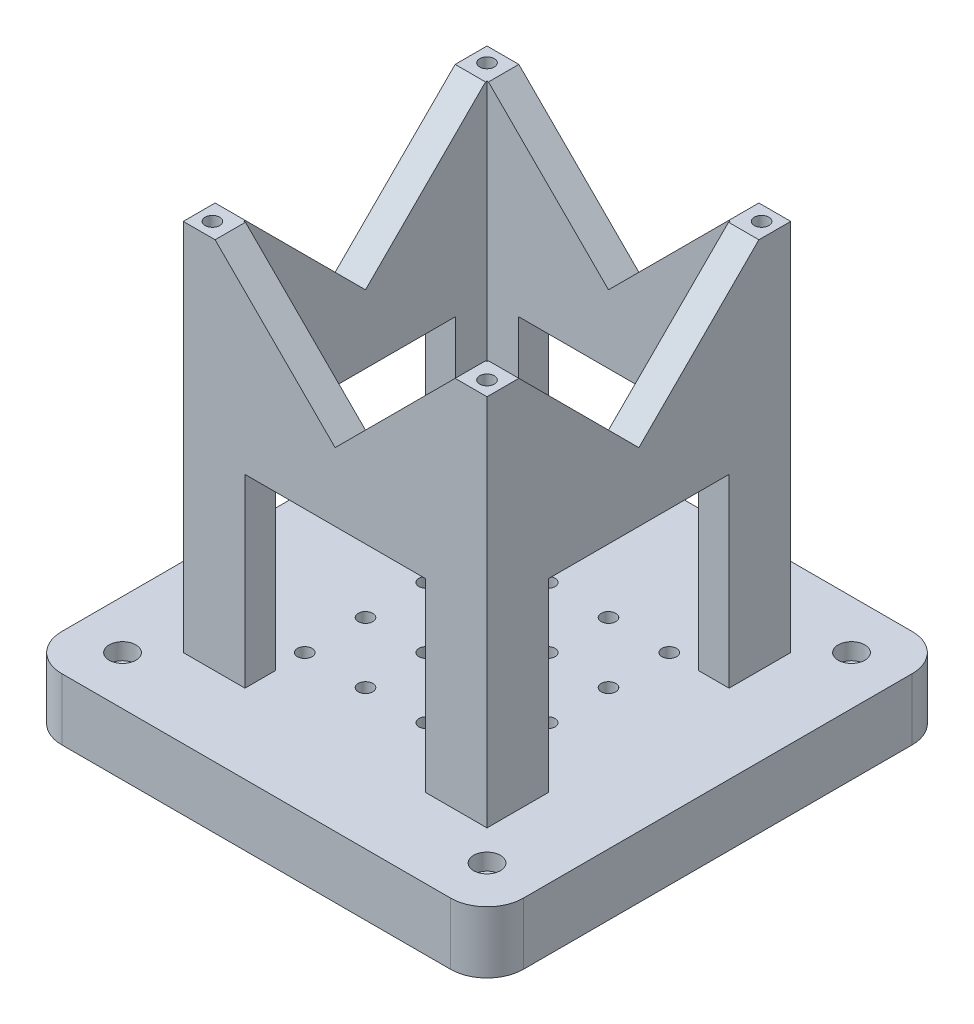
SolidWorks part; units mm, degrees
ref_plane "Front Plane" through (0, 0, 0) normal (0, 0, 1) x (1, 0, 0)
ref_plane "Top Plane" through (0, 0, 0) normal (0, 1, 0) x (1, 0, 0)
ref_plane "Right Plane" through (0, 0, 0) normal (1, 0, 0) x (0, 0, -1)
sketch "Sketch2" plane through (0, 0, 0) normal (0, 1, 0) x (1, 0, 0)
  line L1 (15, 0) -> (175, 0)
  line L2 (0, 15) -> (0, 175)
  line L3 (15, 190) -> (175, 190)
  line L4 (190, 15) -> (190, 175)
  arc A0 (15, 190) -> (0, 175) centre (15, 175) ccw
  arc A1 (0, 15) -> (15, 0) centre (15, 15) ccw
  arc A2 (175, 0) -> (190, 15) centre (175, 15) ccw
  arc A3 (175, 190) -> (190, 175) centre (175, 175) cw
  point P6 (0, 190)
  point P9 (0, 0)
  point P12 (190, 0)
  point P15 (190, 190)
  dimension "D3" = 15
  dimension "D1" = 190
  dimension "D2" = 190
extrude "Extrude2" add sketch "Sketch2" along normal blind 25.4
sketch "Sketch3" plane through (0, 25.4, 0) normal (0, 1, 0) x (-1, 0, 0)
  line L1 (-157.5, -157.5) -> (-32.5, -157.5)
  line L2 (-157.5, -157.5) -> (-157.5, -32.5)
  line L3 (-157.5, -32.5) -> (-32.5, -32.5)
  line L4 (-32.5, -157.5) -> (-32.5, -32.5)
  line L8 (-32.5, -157.5) -> (0, -157.5) construction
  line L9 (0, -175) -> (0, -15) construction
  line L10 (-157.5, -157.5) -> (-190, -157.5) construction
  line L11 (-190, -15) -> (-190, -175) construction
  line L12 (-157.5, -32.5) -> (-157.5, 0) construction
  line L13 (-15, 0) -> (-175, 0) construction
  line L14 (-157.5, -157.5) -> (-157.5, -190) construction
  line L15 (-175, -190) -> (-15, -190) construction
  dimension "D1" = 125
  dimension "D2" = 125
extrude "Extrude3" add sketch "Sketch3" along normal blind 153.67
sketch "Sketch4" plane through (0, 179.07, 0) normal (0, 1, 0) x (-1, 0, 0)
  line L0 (-157.5, -32.5) -> (-157.5, -157.5) construction
  line L1 (-145, -145) -> (-45, -145)
  line L2 (-145, -145) -> (-145, -45)
  line L3 (-145, -45) -> (-45, -45)
  line L4 (-45, -145) -> (-45, -45)
  line L5 (-157.5, -157.5) -> (-32.5, -157.5) construction
  line L6 (-32.5, -157.5) -> (-32.5, -32.5) construction
  line L7 (-32.5, -32.5) -> (-157.5, -32.5) construction
  point P4 (-157.5, -95)
  dimension "D1" = 12.5
  dimension "D2" = 12.5
  dimension "D3" = 12.5
  dimension "D4" = 12.5
extrude "Cut-Extrude1" cut sketch "Sketch4" against normal blind 153.67
sketch "Sketch5" plane through (0, 0, -32.5) normal (0, 0, 1) x (1, 0, 0)
  line L0 (45.6086, 179.07) -> (144.3914, 179.07)
  line L1 (32.5, 179.07) -> (157.5, 179.07) construction
  line L2 (144.3914, 179.07) -> (95, 129.6786)
  line L3 (95, 129.6786) -> (45.6086, 179.07)
  line L4 (32.5, 179.07) -> (32.5, 25.4) construction
  line L5 (157.5, 179.07) -> (157.5, 25.4) construction
  line L6 (15, 25.4) -> (175, 25.4) construction
  line L7 (57.9, 101.6) -> (132.1, 101.6)
  line L8 (57.9, 101.6) -> (57.9, 25.4)
  line L9 (57.9, 25.4) -> (132.1, 25.4)
  line L10 (132.1, 101.6) -> (132.1, 25.4)
  line L11 (32.5, 129.6786) -> (157.5, 129.6786) construction
  point P17 (95, 129.6786)
  dimension "D1" = 135
  dimension "D3" = 49.3914
  dimension "D4" = 25.4
  dimension "D5" = 25.4
  dimension "D6" = 76.2
extrude "Cut-Extrude2" cut sketch "Sketch5" against normal through all
sketch "Sketch6" plane through (157.5, 0, 0) normal (1, 0, 0) x (0, 0, -1)
  line L0 (45.6086, 179.07) -> (144.3914, 179.07)
  line L1 (32.5, 179.07) -> (157.5, 179.07) construction
  line L2 (144.3914, 179.07) -> (95, 129.6786)
  line L3 (95, 129.6786) -> (45.6086, 179.07)
  line L6 (175, 25.4) -> (15, 25.4) construction
  line L7 (132.1, 101.6) -> (57.9, 101.6)
  line L8 (132.1, 101.6) -> (132.1, 25.4)
  line L9 (132.1, 25.4) -> (57.9, 25.4)
  line L10 (57.9, 101.6) -> (57.9, 25.4)
  line L11 (157.5, 179.07) -> (157.5, 25.4) construction
  line L12 (32.5, 179.07) -> (32.5, 25.4) construction
  line L13 (32.5, 179.07) -> (32.5, 25.4) construction
  line L14 (32.5, 129.6786) -> (157.5, 129.6786) construction
  line L15 (157.5, 179.07) -> (157.5, 25.4) construction
  point P19 (95, 129.6786)
  dimension "D1" = 135
  dimension "D3" = 49.3914
  dimension "D4" = 25.4
  dimension "D5" = 25.4
  dimension "D6" = 76.2
  dimension "D7" = 90
extrude "Cut-Extrude3" cut sketch "Sketch6" against normal through all
hole_wizard "M6 螺纹孔3" positions "Sketch8" profile "Sketch7" tap size "M6" standard "GB"
sketch "Sketch8" plane through (0, 179.07, 0) normal (0, 1, 0) x (-1, 0, 0)
  line L0 (-157.5, -157.5) -> (-144.3914, -157.5) construction
  line L1 (-157.5, -144.3914) -> (-157.5, -157.5) construction
  line L2 (-144.3914, -32.5) -> (-157.5, -32.5) construction
  line L3 (-157.5, -32.5) -> (-157.5, -45.6086) construction
  line L5 (-32.5, -45.6086) -> (-32.5, -32.5) construction
  line L6 (-32.5, -157.5) -> (-32.5, -144.3914) construction
  line L7 (-45.6086, -157.5) -> (-32.5, -157.5) construction
  line L8 (-32.5, -32.5) -> (-45.6086, -32.5) construction
  point P0 (-151.5, -151.5)
  point P1 (-151.5, -38.5)
  point P2 (-38.5, -38.5)
  point P3 (-38.5, -151.5)
  point P4 (-150.9457, -157.5)
  dimension "D1" = 6
  dimension "D2" = 6
  dimension "D3" = 6
  dimension "D4" = 6
  dimension "D5" = 6
  dimension "D6" = 6
  dimension "D7" = 6
  dimension "D8" = 6
sketch "Sketch7" plane through (151.5, 179.07, -151.5) normal (1, 0, 0) x (0, 0, 1)
  line L0 (0, 0) -> (0, 16.5022)
  line L1 (0, 16.5022) -> (2.5, 15)
  line L2 (2.5, 15) -> (2.5, 12)
  line L3 (2.5, 12) -> (3, 12)
  line L4 (3, 12) -> (3, 0)
  line L5 (3, 0) -> (0, 0)
  line L10 (0, 16.5022) -> (-2.5, 15) construction
  line L11 (0, -6.35) -> (0, 107.95) construction
  dimension "Tap Drill Dia." = 5
  dimension "Tap Drill Depth" = 15
  dimension "Thread Major Dia." = 6
  dimension "Thread Depth" = 12
  dimension "Drill Angle" = 118
hole_wizard "打孔尺寸(%根据)内六角圆柱头螺钉的类型1" positions "Sketch10" profile "Sketch9" counterbore size "M6" standard "GB" end condition through all
sketch "Sketch10" plane through (0, 25.4, 0) normal (0, 1, 0) x (-1, 0, 0)
  line L4 (-170, -170) -> (-170, -20) construction
  line L5 (-170, -20) -> (-20, -20) construction
  line L6 (-20, -20) -> (-20, -170) construction
  line L7 (-20, -170) -> (-170, -170) construction
  line L9 (-132.1, -170) -> (-132.1, -157.5) construction
  line L11 (-170, -148.8083) -> (-157.5, -148.8083) construction
  line L12 (-157.5, -95) -> (-157.5, -144.3914) construction
  line L14 (-132.1, -20) -> (-132.1, -32.5) construction
  line L15 (-95, -32.5) -> (-144.3914, -32.5) construction
  point P0 (-170, -20)
  point P1 (-170, -170)
  point P2 (-20, -170)
  point P3 (-20, -20)
  dimension "D1" = 150
sketch "Sketch9" plane through (170, 25.4, -20) normal (1, 0, 0) x (0, 0, 1)
  line L0 (0, 0) -> (0, 25.4)
  line L1 (0, 25.4) -> (3.3, 25.4)
  line L3 (3.3, 25.4) -> (3.3, 6.8)
  line L4 (3.3, 6.8) -> (5.5, 6.8)
  line L5 (5.5, 6.8) -> (5.5, 0)
  line L7 (5.5, 0) -> (0, 0)
  line L11 (0, -6.35) -> (0, 107.95) construction
  dimension "Thru Hole Dia." = 6.6
  dimension "Thru Hole Depth" = 25.4
  dimension "C'Bore Dia." = 11
  dimension "C'Bore Depth" = 6.8
hole_wizard "M6 螺纹孔2" positions "Sketch12" profile "Sketch11" tap size "M6" standard "GB" end condition through all
sketch "Sketch12" plane through (0, 25.4, 0) normal (0, 1, 0) x (-1, 0, 0)
  line L7 (-57.9, -145) -> (-45, -145) construction
  line L8 (-45, -145) -> (-45, -132.1) construction
  point P0 (-57.5, -132.5)
  dimension "D1" = 12.5
  dimension "D2" = 12.5
sketch "Sketch11" plane through (57.5, 25.4, -132.5) normal (1, 0, 0) x (0, 0, 1)
  line L0 (0, 0) -> (0, 25.4)
  line L1 (0, 25.4) -> (3, 25.4)
  line L2 (3, 25.4) -> (3, 0)
  line L5 (3, 0) -> (0, 0)
  line L11 (0, -6.35) -> (0, 107.95) construction
  dimension "Thread Major Dia." = 6
  dimension "Thru Tap Drill Depth" = 25.4
pattern_linear "LPattern2" count 4 spacing 25 along (1, 0, 0) count 4 spacing 25 along (0, 0, 1) of "M6 螺纹孔2"
